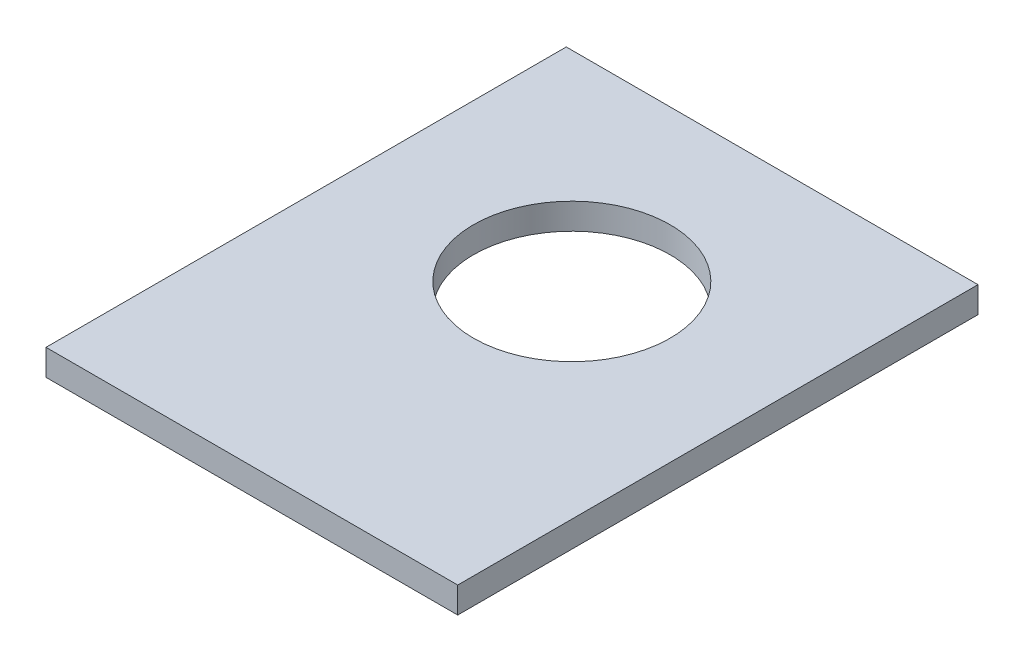
SolidWorks part; units mm, degrees
material "1023 Carbon Steel Sheet (SS)"
ref_plane "Front Plane" through (0, 0, 0) normal (0, 0, 1) x (1, 0, 0)
ref_plane "Top Plane" through (0, 0, 0) normal (0, 1, 0) x (1, 0, 0)
ref_plane "Right Plane" through (0, 0, 0) normal (1, 0, 0) x (0, 0, -1)
sketch "Sketch1" plane through (0, 0, 0) normal (0, 1, 0) x (1, 0, 0)
  line L0 (12.5629, -31.75) -> (12.5629, 0) construction
  line L1 (0, 0) -> (25.1258, 0)
  line L2 (0, 0) -> (0, -31.75)
  line L3 (0, -31.75) -> (25.1258, -31.75)
  line L4 (25.1258, 0) -> (25.1258, -31.75)
  circle A0 centre (12.5629, -12.2246) radius 6
  point P8 (12.5629, -31.75)
  point P10 (12.5629, -12.2246)
extrude "Boss-Extrude1" add sketch "Sketch1" along normal blind 1.5875
